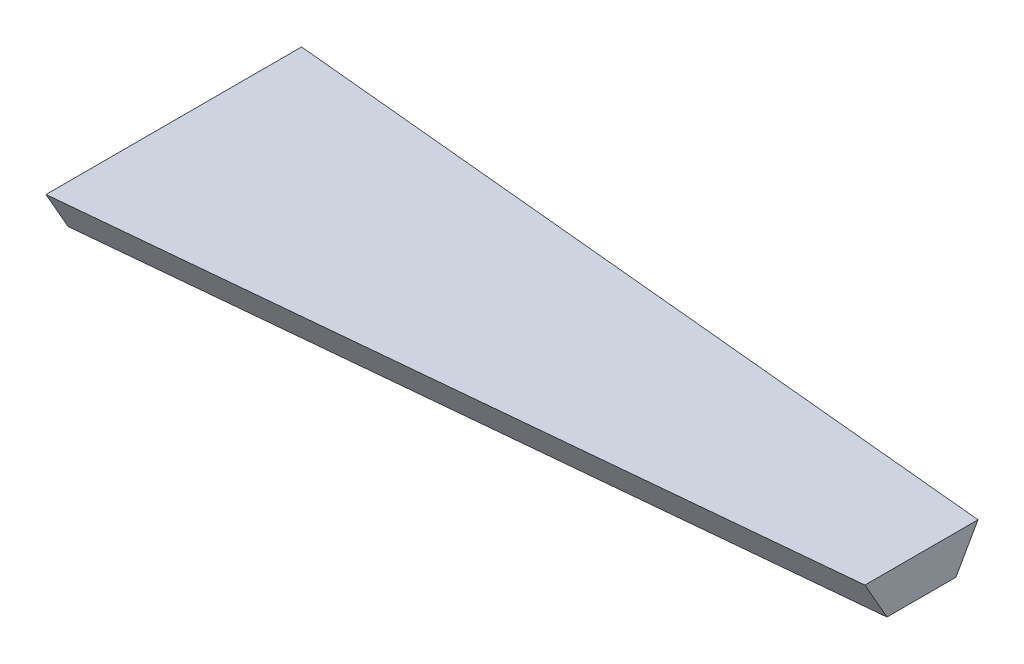
SolidWorks part; units mm, degrees
ref_plane "Front Plane" through (0, 0, 0) normal (0, 0, 1) x (1, 0, 0)
ref_plane "Top Plane" through (0, 0, 0) normal (0, 1, 0) x (1, 0, 0)
ref_plane "Right Plane" through (0, 0, 0) normal (1, 0, 0) x (0, 0, -1)
sketch "Sketch1" plane through (0, 0, 0) normal (0, 1, 0) x (1, 0, 0)
  line L0 (0, 0) -> (0, -103.8354)
  line L1 (0, -103.8354) -> (367.2456, -68.8404)
  line L2 (367.2456, -68.8404) -> (367.2456, -34.9949)
  line L3 (367.2456, -34.9949) -> (0, 0)
  dimension "Crosscut Angle" = 95.443
  dimension "Crosscut Angle 2" = 95.443
  dimension "BISW" = 33.8455
  dimension "Cut To Length" = 367.2456
extrude "Boss-Extrude1" add sketch "Sketch1" along normal blind 19.05 draft 29.547 draft outward yes
sketch "Sketch2" plane through (0, 0, 0) normal (0, 0, 1) x (1, 0, 0)
  line L0 (0, 0) -> (367.2456, 0)
  line L1 (0, 0) -> (0, 100.342)
  line L2 (367.2456, 0) -> (367.2456, 100.342)
  line L3 (0, 100.342) -> (367.2456, 100.342)
extrude "Cut-Extrude1" cut sketch "Sketch2" against normal through all and the other way through all flip side to cut
equation "\"Crosscut\"=88.0525"
